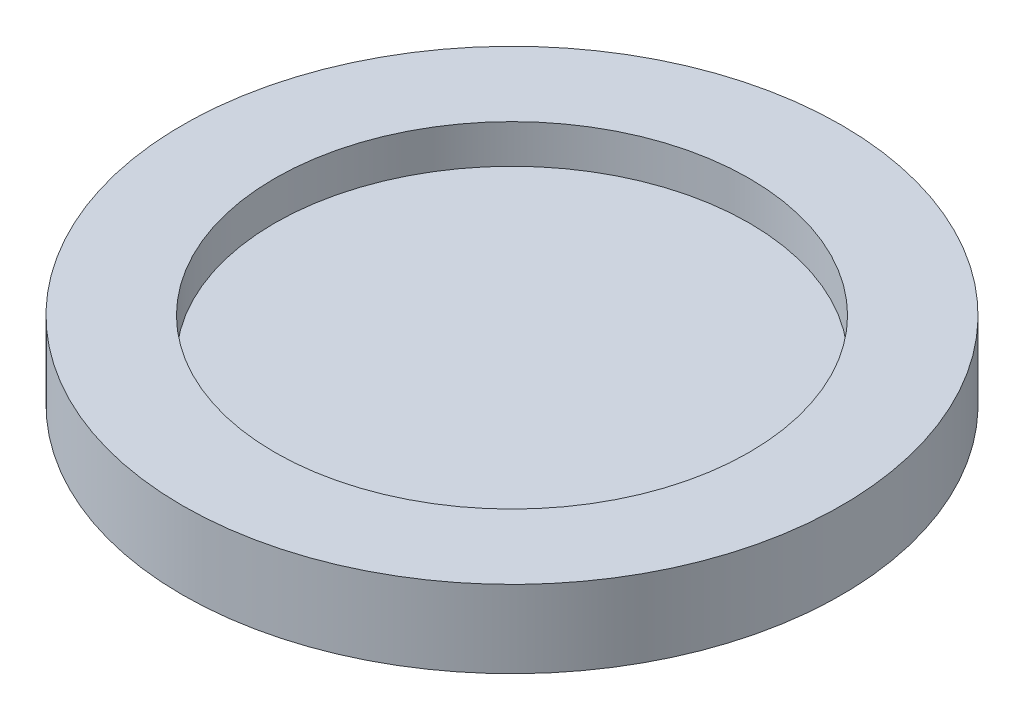
SolidWorks part; units mm, degrees
ref_plane "Front Plane" through (0, 0, 0) normal (0, 0, 1) x (1, 0, 0)
ref_plane "Top Plane" through (0, 0, 0) normal (0, 1, 0) x (1, 0, 0)
ref_plane "Right Plane" through (0, 0, 0) normal (1, 0, 0) x (0, 0, -1)
sketch "Sketch1" plane through (0, 0, 0) normal (0, 1, 0) x (1, 0, 0)
  circle A0 centre (0, 0) radius 9.375
  dimension "D1" = 18.75
extrude "Boss-Extrude1" add sketch "Sketch1" along normal blind 2.2
sketch "Sketch2" plane through (0, 2.2, 0) normal (0, 1, 0) x (1, 0, 0)
  circle A0 centre (0, 0) radius 6.75
  dimension "D1" = 13.5
extrude "Cut-Extrude1" cut sketch "Sketch2" against normal blind 1.1
